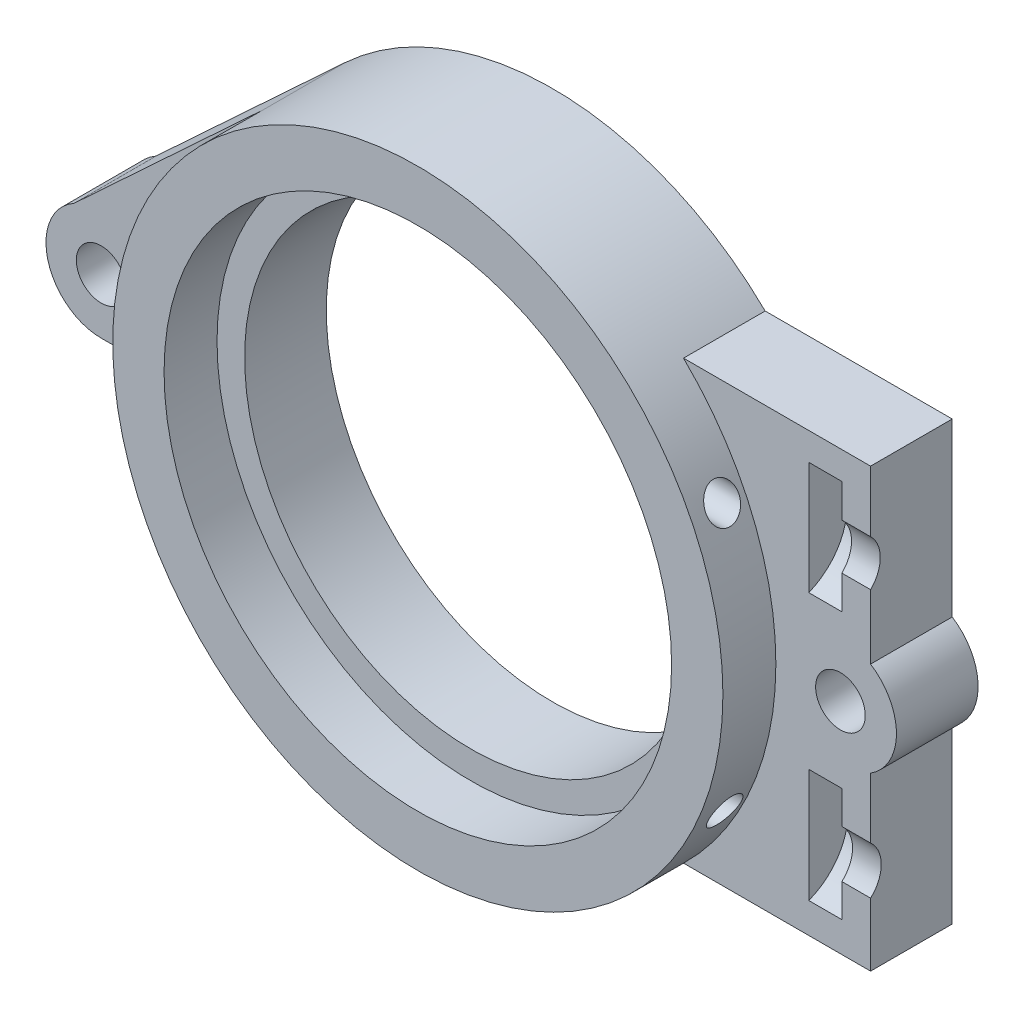
SolidWorks part; units mm, degrees
material "ABS PC"
ref_plane "Alzado" through (0, 0, 0) normal (0, 0, 1) x (1, 0, 0)
ref_plane "Planta" through (0, 0, 0) normal (0, 1, 0) x (1, 0, 0)
ref_plane "Vista lateral" through (0, 0, 0) normal (1, 0, 0) x (0, 0, -1)
sketch "Croquis1" plane through (0, 0, 0) normal (0, 0, 1) x (1, 0, 0)
  line L0 (-35.9552, 4.3557) -> (-18.8079, 20.2678) construction
  line L1 (-35.9552, 4.3557) -> (-18.8079, 20.2678)
  line L2 (-33.5, -5) -> (-27.1942, -5) construction
  line L3 (33.5, 0) -> (33.5, 27.3668) construction
  line L4 (36.2316, 4.2795) -> (36.2316, 19.82)
  line L5 (-33.5, -5) -> (-27.1942, -5)
  line L6 (0, 0) -> (33.5, 0) construction
  line L7 (36.2316, 19.82) -> (19.2793, 19.82)
  line L10 (36.8806, 3.684) -> (18.6947, 20.3723) construction
  line L11 (36.2316, -4.2795) -> (36.2316, -19.82)
  line L12 (36.2316, -19.82) -> (19.2793, -19.82)
  arc A0 (-35.9552, 4.3557) -> (-33.5, -5) centre (-33.5, 0) ccw construction
  arc A1 (-27.1942, -5) -> (19.2793, -19.82) centre (0, 0) ccw
  circle A4 centre (-33.5, 0) radius 2.25 construction
  circle A5 centre (33.5, 0) radius 2.25 construction
  arc A6 (-35.9552, 4.3557) -> (-33.5, -5) centre (-33.5, 0) ccw
  circle A7 centre (0, 0) radius 27.65 construction
  arc A8 (19.2793, 19.82) -> (-18.8079, 20.2678) centre (0, 0) ccw
  arc A9 (36.2316, -4.2795) -> (36.2316, 4.2795) centre (33.5, 0) ccw
  circle A10 centre (-33.5, 0) radius 2.25
  circle A11 centre (33.5, 0) radius 2.25
  dimension "D1" = 15.5405
  dimension "D2" = 16.9523
extrude "Saliente-Extruir1" add sketch "Croquis1" along normal blind 7.4
sketch "Croquis4" plane through (33.6316, 0, 0) normal (1, 0, 0) x (0, -0.9997, -0.0262)
  circle A0 centre (-12.4457, -9.0989) radius 5.5 construction
  circle A1 centre (-12.4457, -9.0989) radius 5.5
  circle A2 centre (11.6776, -9.6415) radius 5.5 construction
  circle A3 centre (11.6776, -9.6415) radius 5.5
extrude "Cortar-Extruir2" cut sketch "Croquis4" against normal blind 3
sketch "Croquis5" plane through (36.2316, 0, 0) normal (-1, 0, 0) x (0, -1, 0)
  circle A0 centre (-12.2034, 9.4214) radius 2.9 construction
  circle A1 centre (-12.2034, 9.4214) radius 2.9
  circle A2 centre (11.9258, 9.3328) radius 2.9 construction
  circle A3 centre (11.9258, 9.3328) radius 2.9
extrude "Cortar-Extruir3" cut sketch "Croquis5" along normal blind 4
sketch "Croquis2" plane through (0, 0, 7.4) normal (0, 0, 1) x (1, 0, 0)
  circle A3 centre (0, 0) radius 20.5
  dimension "D1" = 41
extrude "Cortar-Extruir1" cut sketch "Croquis2" against normal through all contours A3
sketch "Croquis3" plane through (0, 0, 7.4) normal (0, 0, 1) x (1, 0, 0)
  circle A1 centre (0, 0) radius 23
  circle A2 centre (0, 0) radius 27.65 construction
  circle A3 centre (0, 0) radius 27.65
  dimension "D1" = 46
extrude "Saliente-Extruir2" add sketch "Croquis3" along normal blind 4.8
sketch "Croquis6" plane through (26.0316, 0, 0) normal (-1, 0, 0) x (0, -1, 0)
  circle A0 centre (-12.2034, 9.4214) radius 1.5 construction
  circle A1 centre (-12.2034, 9.4214) radius 1.5
  circle A2 centre (11.9258, 9.3328) radius 1.5 construction
  circle A3 centre (11.9258, 9.3328) radius 1.5
extrude "Cortar-Extruir4" cut sketch "Croquis6" against normal blind 9 and the other way blind 20
